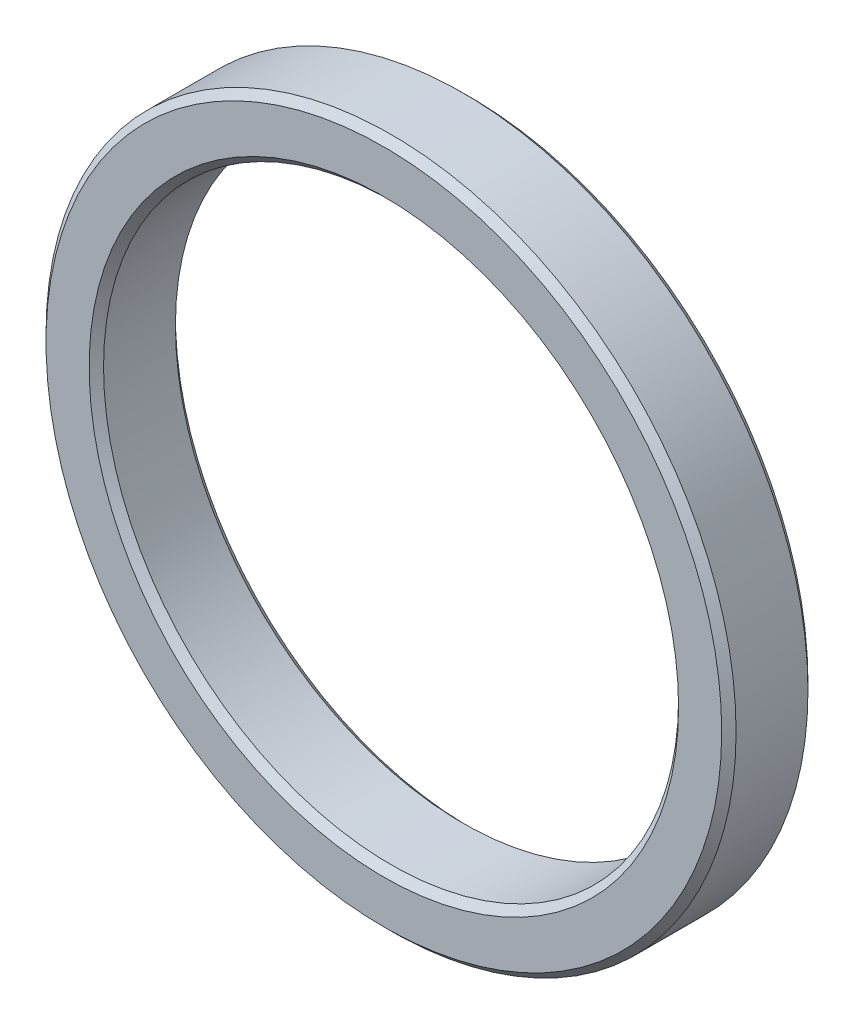
SolidWorks part; units mm, degrees
ref_plane "前视基准面" through (0, 0, 0) normal (0, 0, 1) x (1, 0, 0)
ref_plane "上视基准面" through (0, 0, 0) normal (0, 1, 0) x (1, 0, 0)
ref_plane "右视基准面" through (0, 0, 0) normal (1, 0, 0) x (0, 0, -1)
sketch "草图1" plane through (0, 0, 0) normal (0, 0, 1) x (1, 0, 0)
  circle A0 centre (0, 0) radius 20
  circle A1 centre (0, 0) radius 24
  dimension "D1" = 48
extrude "拉伸1" add sketch "草图1" along normal blind 6
chamfer "倒角1" distance 0.5 angle 45 4 edges at (24, 0, 0) (24, 0, 6) (20, 0, 0) (20, 0, 6)
